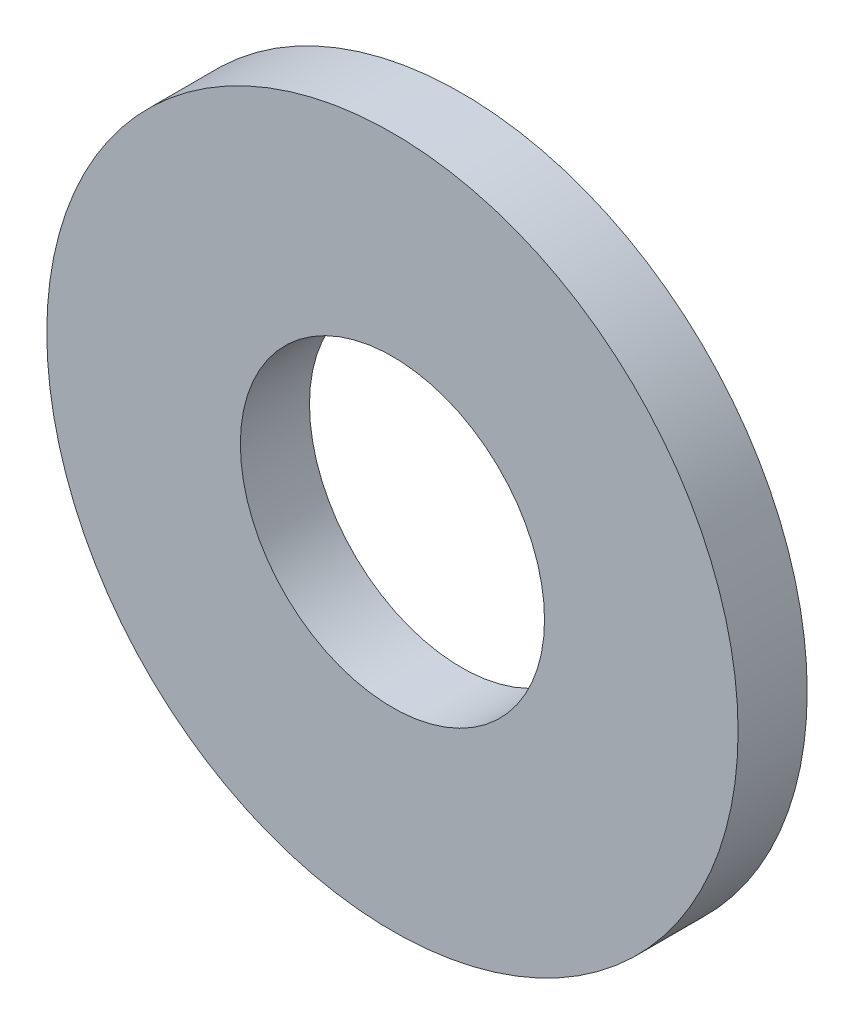
SolidWorks part; units mm, degrees
ref_plane "Front Plane" through (0, 0, 0) normal (0, 0, 1) x (1, 0, 0)
ref_plane "Top Plane" through (0, 0, 0) normal (0, 1, 0) x (1, 0, 0)
ref_plane "Right Plane" through (0, 0, 0) normal (1, 0, 0) x (0, 0, -1)
sketch "Washer_profile" plane through (0, 0, 0) normal (0, 0, 1) x (1, 0, 0)
  circle A0 centre (0, 0) radius 2.5
  circle A1 centre (0, 0) radius 1.1
  dimension "D1" = 5
  dimension "D2" = 2.2
extrude "Washer" add sketch "Washer_profile" along normal blind 0.5
